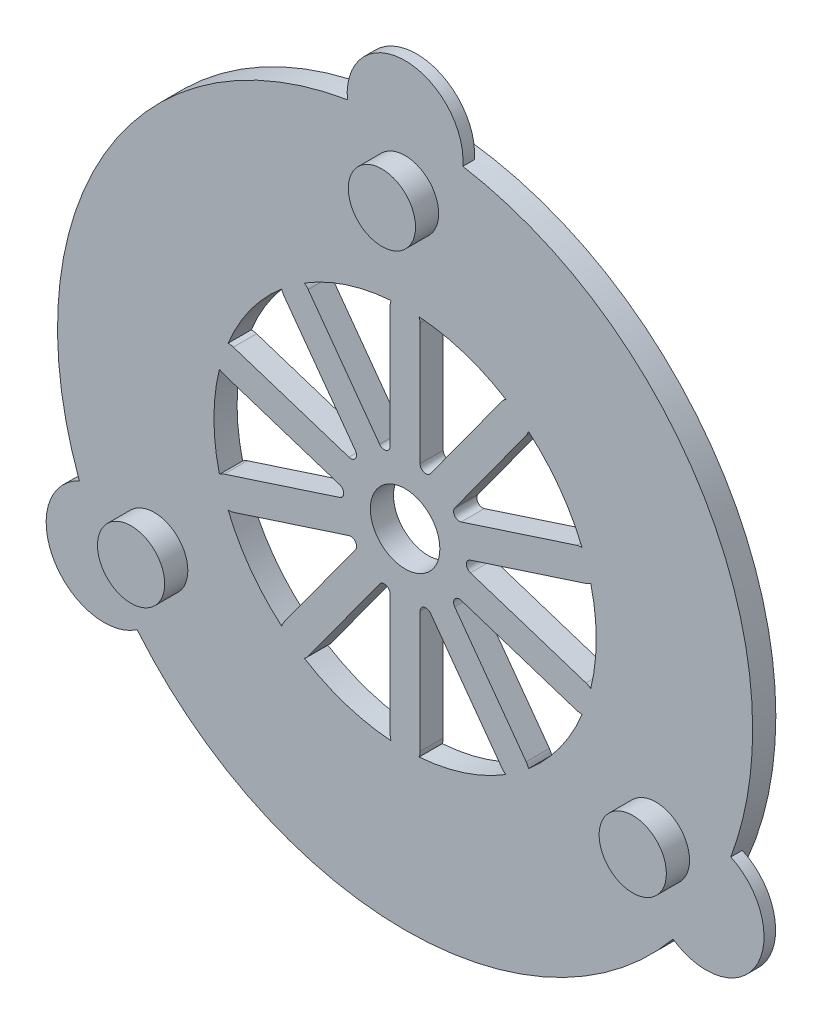
SolidWorks part; units mm, degrees
ref_plane "Спереди" through (0, 0, 0) normal (0, 0, 1) x (1, 0, 0)
ref_plane "Сверху" through (0, 0, 0) normal (0, 1, 0) x (1, 0, 0)
ref_plane "Справа" through (0, 0, 0) normal (1, 0, 0) x (0, 0, -1)
sketch "Sketch1" plane through (0, 0, 0) normal (0, 0, 1) x (1, 0, 0)
  line L0 (3.9, 6.755) -> (7.8, 0) construction
  line L2 (5.85, 10.1325) -> (11.7, 0) construction
  line L4 (7.8, 13.51) -> (15.6, 0) construction
  circle A61 centre (0, 0) radius 20
  circle A131 centre (0, 0) radius 1.25
  circle A484 centre (3.9, 0) radius 1.25
  circle A485 centre (7.8, 0) radius 1.25
  circle A486 centre (11.7, 0) radius 1.25
  circle A487 centre (15.6, 0) radius 1.25
  circle A488 centre (1.95, -3.3775) radius 1.25
  circle A489 centre (3.9, -6.755) radius 1.25
  circle A490 centre (5.85, -10.1325) radius 1.25
  circle A491 centre (7.8, -13.51) radius 1.25
  circle A492 centre (-1.95, -3.3775) radius 1.25
  circle A493 centre (-3.9, -6.755) radius 1.25
  circle A494 centre (-5.85, -10.1325) radius 1.25
  circle A495 centre (-7.8, -13.51) radius 1.25
  circle A496 centre (-3.9, 0) radius 1.25
  circle A497 centre (-7.8, 0) radius 1.25
  circle A498 centre (-11.7, 0) radius 1.25
  circle A499 centre (-15.6, 0) radius 1.25
  circle A500 centre (-1.95, 3.3775) radius 1.25
  circle A501 centre (-3.9, 6.755) radius 1.25
  circle A502 centre (-5.85, 10.1325) radius 1.25
  circle A503 centre (-7.8, 13.51) radius 1.25
  circle A504 centre (1.95, 3.3775) radius 1.25
  circle A505 centre (3.9, 6.755) radius 1.25
  circle A506 centre (5.85, 10.1325) radius 1.25
  circle A507 centre (7.8, 13.51) radius 1.25
  circle A508 centre (5.85, 3.3775) radius 1.25
  circle A509 centre (7.8, 6.755) radius 1.25
  circle A510 centre (9.75, 3.3775) radius 1.25
  circle A511 centre (11.7, 6.755) radius 1.25
  circle A512 centre (9.7491, 10.1341) radius 1.25
  circle A513 centre (13.6509, 3.3759) radius 1.25
  circle A514 centre (5.85, -3.3791) radius 1.25
  circle A515 centre (9.75, -3.3791) radius 1.25
  circle A516 centre (7.8, -6.7566) radius 1.25
  circle A517 centre (11.7, -6.7566) radius 1.25
  circle A518 centre (9.7491, -10.1356) radius 1.25
  circle A519 centre (13.6509, -3.3775) radius 1.25
  circle A520 centre (-0.0013, -6.7573) radius 1.25
  circle A521 centre (1.9487, -10.1348) radius 1.25
  circle A522 centre (-1.9513, -10.1348) radius 1.25
  circle A523 centre (-0.0013, -13.5123) radius 1.25
  circle A524 centre (-3.9032, -13.5123) radius 1.25
  circle A525 centre (3.9005, -13.5123) radius 1.25
  circle A526 centre (-5.8527, -3.3791) radius 1.25
  circle A527 centre (-7.8027, -6.7566) radius 1.25
  circle A528 centre (-9.7527, -3.3791) radius 1.25
  circle A529 centre (-11.7027, -6.7566) radius 1.25
  circle A530 centre (-13.6536, -3.3775) radius 1.25
  circle A531 centre (-9.7518, -10.1356) radius 1.25
  circle A532 centre (-5.8527, 3.3775) radius 1.25
  circle A533 centre (-9.7527, 3.3775) radius 1.25
  circle A534 centre (-7.8027, 6.755) radius 1.25
  circle A535 centre (-11.7027, 6.755) radius 1.25
  circle A536 centre (-9.7518, 10.1341) radius 1.25
  circle A537 centre (-13.6536, 3.3759) radius 1.25
  circle A538 centre (-0.0014, 6.7558) radius 1.25
  circle A539 centre (-1.9514, 10.1333) radius 1.25
  circle A540 centre (1.9486, 10.1333) radius 1.25
  circle A541 centre (-0.0014, 13.5108) radius 1.25
  circle A542 centre (3.9005, 13.5108) radius 1.25
  circle A543 centre (-3.9032, 13.5108) radius 1.25
  circle A544 centre (13.65, -1.1258) radius 2.2517 construction
  circle A545 centre (11.7009, -4.5044) radius 2.2522 construction
  circle A546 centre (9.75, -7.8834) radius 2.2522 construction
  circle A547 centre (7.7987, -11.2591) radius 2.2509 construction
  circle A548 centre (13.65, -1.1258) radius 0.65
  circle A549 centre (11.7009, -4.5044) radius 0.65
  circle A550 centre (9.75, -7.8834) radius 0.65
  circle A551 centre (7.7987, -11.2591) radius 0.65
  circle A552 centre (9.75, -1.1258) radius 0.65
  circle A553 centre (7.8009, -4.5044) radius 0.65
  circle A554 centre (5.85, -7.8834) radius 0.65
  circle A555 centre (3.8987, -11.2591) radius 0.65
  circle A556 centre (5.85, -1.1258) radius 0.65
  circle A557 centre (3.9009, -4.5044) radius 0.65
  circle A558 centre (1.95, -7.8834) radius 0.65
  circle A559 centre (-0.0013, -11.2591) radius 0.65
  circle A560 centre (1.95, -1.1258) radius 0.65
  circle A561 centre (0.0009, -4.5044) radius 0.65
  circle A562 centre (-1.95, -7.8834) radius 0.65
  circle A563 centre (-3.9013, -11.2591) radius 0.65
  circle A564 centre (-1.95, -1.1258) radius 0.65
  circle A565 centre (-3.8991, -4.5044) radius 0.65
  circle A566 centre (-5.85, -7.8834) radius 0.65
  circle A567 centre (-7.8013, -11.2591) radius 0.65
  circle A568 centre (-5.85, -1.1258) radius 0.65
  circle A569 centre (-7.7991, -4.5044) radius 0.65
  circle A570 centre (-9.75, -7.8834) radius 0.65
  circle A572 centre (-9.75, -1.1258) radius 0.65
  circle A573 centre (-11.6991, -4.5044) radius 0.65
  circle A576 centre (-13.65, -1.1258) radius 0.65
  circle A587 centre (0, 2.2517) radius 2.2517 construction
  circle A588 centre (0, 2.2517) radius 0.65
  circle A589 centre (3.9, 2.2517) radius 0.65
  circle A590 centre (7.8, 2.2517) radius 0.65
  circle A591 centre (11.7, 2.2517) radius 0.65
  circle A592 centre (15.6, 2.2517) radius 0.65
  circle A593 centre (1.9491, 5.6297) radius 2.2522 construction
  circle A594 centre (1.9491, 5.6297) radius 0.65
  circle A595 centre (5.8491, 5.6297) radius 0.65
  circle A596 centre (9.7491, 5.6297) radius 0.65
  circle A597 centre (13.6491, 5.6297) radius 0.65
  circle A598 centre (3.8991, 9.0072) radius 2.2522 construction
  circle A599 centre (3.8991, 9.0072) radius 0.65
  circle A600 centre (7.7991, 9.0072) radius 0.65
  circle A601 centre (11.6991, 9.0072) radius 0.65
  circle A602 centre (5.85, 12.3842) radius 2.2517 construction
  circle A603 centre (5.85, 12.3842) radius 0.65
  circle A604 centre (9.75, 12.3842) radius 0.65
  circle A605 centre (5.85, -14.6358) radius 0.65
  circle A606 centre (1.9509, -14.6353) radius 0.65
  circle A607 centre (-1.9491, -14.6353) radius 0.65
  circle A608 centre (-5.85, -14.6358) radius 0.65
  circle A609 centre (-15.6, 2.2517) radius 0.65
  circle A610 centre (-13.65, 5.6281) radius 0.65
  circle A611 centre (-11.7, 9.0056) radius 0.65
  circle A612 centre (-9.75, 12.3842) radius 0.65
  circle A613 centre (-5.85, 12.3842) radius 0.65
  circle A614 centre (-1.95, 12.3842) radius 0.65
  circle A615 centre (1.95, 12.3842) radius 0.65
  circle A616 centre (-7.8, 9.0056) radius 0.65
  circle A617 centre (-9.75, 5.6281) radius 0.65
  circle A618 centre (-11.7, 2.2517) radius 0.65
  circle A619 centre (-3.9, 9.0056) radius 0.65
  circle A620 centre (-5.85, 5.6281) radius 0.65
  circle A621 centre (-7.8, 2.2517) radius 0.65
  circle A622 centre (0, 9.0056) radius 0.65
  circle A623 centre (-1.95, 5.6281) radius 0.65
  circle A624 centre (-3.9, 2.2517) radius 0.65
  circle A625 centre (-15.5991, -4.5044) radius 0.65
  circle A626 centre (-13.65, -7.8834) radius 0.65
  circle A627 centre (-17.55, -7.8834) radius 0.65
  circle A628 centre (-19.5013, -11.2591) radius 0.65
  circle A629 centre (-15.6013, -11.2591) radius 0.65
  circle A630 centre (-11.7013, -11.2591) radius 0.65
  point P51 (0, 0)
  point P125 (-0.0013, -0.0008)
  point P231 (0, 0)
  dimension "D1" = 5
  dimension "D3" = 6
  dimension "D5" = 8
  dimension "D7" = 4
  dimension "D11" = 4
  dimension "D2" = 6
  dimension "D6" = 5
  dimension "D8" = 3
  dimension "D9" = 2
  dimension "D4" = 1.3
  dimension "D10" = 3
ref_plane "Plane1" through (0, 0, 10) normal (0, 0, 1) x (1, 0, 0)
sketch "Sketch2" plane through (0, 0, 10) normal (0, 0, 1) x (1, 0, 0)
  line L0 (-0.0032, 16) -> (0, 0) construction
  line L1 (1.2877, 16.0003) -> (1.2909, 0.0003)
  line L2 (-1.2941, 15.9997) -> (-1.2909, -0.0003)
  line L3 (8.3575, 13.7047) -> (-1.0445, 0.7585)
  line L4 (10.4465, 12.1876) -> (1.0445, -0.7585)
  line L5 (9.402, 12.9462) -> (0, 0) construction
  line L6 (14.8168, 6.1749) -> (-0.3991, 1.2276)
  line L7 (15.6151, 3.7197) -> (0.3991, -1.2276)
  line L8 (15.2159, 4.9473) -> (0, 0) construction
  line L9 (15.6165, -3.7135) -> (0.3987, 1.2278)
  line L10 (14.8192, -6.169) -> (-0.3987, -1.2278)
  line L11 (15.2179, -4.9412) -> (0, 0) construction
  line L12 (10.4513, -12.1834) -> (1.0442, 0.759)
  line L13 (8.363, -13.7014) -> (-1.0442, -0.759)
  line L14 (9.4072, -12.9424) -> (0, 0) construction
  line L15 (1.2941, -15.9997) -> (1.2909, 0.0003)
  line L16 (-1.2877, -16.0003) -> (-1.2909, -0.0003)
  line L17 (0.0032, -16) -> (0, 0) construction
  line L18 (-8.3575, -13.7047) -> (1.0445, -0.7585)
  line L19 (-10.4465, -12.1876) -> (-1.0445, 0.7585)
  line L20 (-9.402, -12.9462) -> (0, 0) construction
  line L21 (-14.8168, -6.1749) -> (0.3991, -1.2276)
  line L22 (-15.6151, -3.7197) -> (-0.3991, 1.2276)
  line L23 (-15.2159, -4.9473) -> (0, 0) construction
  line L24 (-15.6165, 3.7135) -> (-0.3987, -1.2278)
  line L25 (-14.8192, 6.169) -> (0.3987, 1.2278)
  line L26 (-15.2179, 4.9412) -> (0, 0) construction
  line L27 (-10.4513, 12.1834) -> (-1.0442, -0.759)
  line L28 (-8.363, 13.7014) -> (1.0442, 0.759)
  line L29 (-9.4072, 12.9424) -> (0, 0) construction
  circle A52 centre (0, 0) radius 16.85 construction
  circle A53 centre (0, 0) radius 18.85
  arc A54 (1.2877, 16.0003) -> (-1.2941, 15.9997) centre (-0.0032, 16) ccw
  arc A55 (-1.2909, -0.0003) -> (1.2909, 0.0003) centre (0, 0) ccw
  arc A56 (10.4465, 12.1876) -> (8.3575, 13.7047) centre (9.402, 12.9462) ccw
  arc A57 (-1.0445, 0.7585) -> (1.0445, -0.7585) centre (0, 0) ccw
  arc A58 (15.6151, 3.7197) -> (14.8168, 6.1749) centre (15.2159, 4.9473) ccw
  arc A59 (-0.3991, 1.2276) -> (0.3991, -1.2276) centre (0, 0) ccw
  arc A60 (14.8192, -6.169) -> (15.6165, -3.7135) centre (15.2179, -4.9412) ccw
  arc A61 (0.3987, 1.2278) -> (-0.3987, -1.2278) centre (0, 0) ccw
  arc A62 (8.363, -13.7014) -> (10.4513, -12.1834) centre (9.4072, -12.9424) ccw
  arc A63 (1.0442, 0.759) -> (-1.0442, -0.759) centre (0, 0) ccw
  arc A64 (-1.2877, -16.0003) -> (1.2941, -15.9997) centre (0.0032, -16) ccw
  arc A65 (1.2909, 0.0003) -> (-1.2909, -0.0003) centre (0, 0) ccw
  arc A66 (-10.4465, -12.1876) -> (-8.3575, -13.7047) centre (-9.402, -12.9462) ccw
  arc A67 (1.0445, -0.7585) -> (-1.0445, 0.7585) centre (0, 0) ccw
  arc A68 (-15.6151, -3.7197) -> (-14.8168, -6.1749) centre (-15.2159, -4.9473) ccw
  arc A69 (0.3991, -1.2276) -> (-0.3991, 1.2276) centre (0, 0) ccw
  arc A70 (-14.8192, 6.169) -> (-15.6165, 3.7135) centre (-15.2179, 4.9412) ccw
  arc A71 (-0.3987, -1.2278) -> (0.3987, 1.2278) centre (0, 0) ccw
  arc A72 (-8.363, 13.7014) -> (-10.4513, 12.1834) centre (-9.4072, 12.9424) ccw
  arc A73 (-1.0442, -0.759) -> (1.0442, 0.759) centre (0, 0) ccw
  point P1 (-0.0016, 8)
  point P9 (4.701, 6.4731)
  point P15 (7.608, 2.4737)
  point P21 (7.6089, -2.4706)
  point P27 (4.7036, -6.4712)
  point P33 (0.0016, -8)
  point P39 (-4.701, -6.4731)
  point P45 (-7.608, -2.4737)
  point P51 (-7.6089, 2.4706)
  point P57 (-4.7036, 6.4712)
  point P62 (0, 0)
extrude "Boss-Extrude1" add sketch "Sketch2" along normal blind 2 contours L4 A56 L3 L1 L6 | L1 A54 L2 L28 L3 | L28 A72 L27 L25 L2 | L25 A70 L24 L22 L27 | L22 A68 L21 L19 L24 | L19 A66 L18 L16 L21 | L16 A64 L15 L13 L18 | L13 A62 L12 L10 L15 | L10 A60 L9 L7 L12 | L7 A58 L6 L4 L9
sketch "Sketch3" plane through (0, 0, 12) normal (0, 0, 1) x (1, 0, 0)
  circle A0 centre (0, 0) radius 16.5
  circle A1 centre (0, 0) radius 30
extrude "Boss-Extrude2" add sketch "Sketch3" against normal blind 2
sketch "Sketch4" plane through (0, 0, 12) normal (0, 0, 1) x (1, 0, 0)
  circle A0 centre (0, 0) radius 25 construction
  circle A1 centre (0, 25) radius 2.9
  circle A2 centre (21.6506, -12.5) radius 2.9
  circle A3 centre (-21.6506, -12.5) radius 2.9
  point P11 (0, 0)
  dimension "D1" = 3
extrude "Boss-Extrude3" add sketch "Sketch4" along normal blind 2
sketch "Sketch6" plane through (0, 0, 11) normal (0, 0, -1) x (-1, 0, 0)
  circle A0 centre (0, 30) radius 5
  circle A2 centre (25.9808, -15) radius 5
  circle A3 centre (-25.9808, -15) radius 5
  point P10 (0, 0)
  dimension "D1" = 3
extrude "Boss-Extrude4" add sketch "Sketch6" against normal blind 1
sketch "Sketch5" plane through (0, 0, 10) normal (0, 0, -1) x (-1, 0, 0)
  circle A0 centre (0, 25) radius 3
  circle A1 centre (21.6506, -12.5) radius 3
  circle A2 centre (-21.6506, -12.5) radius 3
sketch "Sketch9" plane through (0, 0, 0) normal (0, 0, 1) x (1, 0, 0)
  line L0 (-7.8, 13.51) -> (-7.8027, 6.755) construction
  line L1 (-9.7518, 10.1341) -> (-5.85, 10.1325) construction
  line L2 (-7.8008, 11.6325) -> (-7.8019, 8.6325) construction
  line L3 (-6.8008, 11.6321) -> (-6.8019, 8.6321)
  line L4 (-8.8008, 11.6329) -> (-8.8019, 8.6329)
  line L5 (-4.9008, 11.6329) -> (-4.9019, 8.6329)
  line L6 (-2.9008, 11.6321) -> (-2.9019, 8.6321)
  line L7 (-3.9008, 11.6325) -> (-3.9019, 8.6325) construction
  line L8 (-1.0008, 11.6329) -> (-1.0019, 8.6329)
  line L9 (0.9992, 11.6321) -> (0.9981, 8.6321)
  line L10 (-0.0008, 11.6325) -> (-0.0019, 8.6325) construction
  line L11 (2.8992, 11.6329) -> (2.8981, 8.6329)
  line L12 (4.8992, 11.6321) -> (4.8981, 8.6321)
  line L13 (3.8992, 11.6325) -> (3.8981, 8.6325) construction
  line L14 (6.7992, 11.6329) -> (6.7981, 8.6329)
  line L15 (8.7992, 11.6321) -> (8.7981, 8.6321)
  line L16 (7.7992, 11.6325) -> (7.7981, 8.6325) construction
  line L17 (-9.7518, 10.1341) -> (-9.7527, 3.3775) construction
  line L18 (-11.7027, 6.755) -> (-7.8027, 6.755) construction
  line L19 (-10.7035, 1.877) -> (-10.702, 4.877)
  line L22 (-9.7527, 3.3775) -> (-5.8527, 3.3775) construction
  line L25 (-7.8027, 6.755) -> (-7.8, 0) construction
  line L26 (-7.8035, 1.8775) -> (-7.8019, 4.8775) construction
  line L27 (-8.8035, 1.878) -> (-8.8019, 4.878)
  line L28 (-6.8035, 1.877) -> (-6.8019, 4.877)
  line L29 (-2.9035, 1.877) -> (-2.9019, 4.877)
  line L30 (-4.9035, 1.878) -> (-4.9019, 4.878)
  line L31 (-3.9035, 1.8775) -> (-3.9019, 4.8775) construction
  line L32 (0.9965, 1.877) -> (0.9981, 4.877)
  line L33 (-1.0035, 1.878) -> (-1.0019, 4.878)
  line L34 (-0.0035, 1.8775) -> (-0.0019, 4.8775) construction
  line L35 (4.8965, 1.877) -> (4.8981, 4.877)
  line L36 (2.8965, 1.878) -> (2.8981, 4.878)
  line L37 (3.8965, 1.8775) -> (3.8981, 4.8775) construction
  line L38 (8.7965, 1.877) -> (8.7981, 4.877)
  line L39 (6.7965, 1.878) -> (6.7981, 4.878)
  line L40 (7.7965, 1.8775) -> (7.7981, 4.8775) construction
  line L41 (12.6965, 1.877) -> (12.6981, 4.877)
  line L42 (10.6965, 1.878) -> (10.6981, 4.878)
  line L43 (11.6965, 1.8775) -> (11.6981, 4.8775) construction
  line L44 (-12.7035, 1.878) -> (-12.7019, 4.878)
  line L45 (-11.7035, 1.8775) -> (-11.702, 4.8775) construction
  line L46 (-9.7527, -3.3791) -> (-5.8527, -3.3791) construction
  line L47 (-7.8, 0) -> (-7.8027, -6.7566) construction
  line L48 (-7.8046, -4.8791) -> (-7.8008, -1.8791) construction
  line L49 (-8.8046, -4.8778) -> (-8.8008, -1.8778)
  line L50 (-6.8046, -4.8804) -> (-6.8008, -1.8804)
  line L51 (-2.9046, -4.8804) -> (-2.9008, -1.8804)
  line L52 (-4.9046, -4.8778) -> (-4.9008, -1.8778)
  line L53 (-3.9046, -4.8791) -> (-3.9008, -1.8791) construction
  line L54 (0.9954, -4.8804) -> (0.9992, -1.8804)
  line L55 (-1.0046, -4.8778) -> (-1.0008, -1.8778)
  line L56 (-0.0046, -4.8791) -> (-0.0008, -1.8791) construction
  line L57 (4.8954, -4.8804) -> (4.8992, -1.8804)
  line L58 (2.8954, -4.8778) -> (2.8992, -1.8778)
  line L59 (3.8954, -4.8791) -> (3.8992, -1.8791) construction
  line L60 (8.7954, -4.8804) -> (8.7992, -1.8804)
  line L61 (6.7954, -4.8778) -> (6.7992, -1.8778)
  line L62 (7.7954, -4.8791) -> (7.7992, -1.8791) construction
  line L63 (12.6954, -4.8804) -> (12.6992, -1.8804)
  line L64 (10.6954, -4.8778) -> (10.6992, -1.8778)
  line L65 (11.6954, -4.8791) -> (11.6992, -1.8791) construction
  line L66 (-10.7046, -4.8804) -> (-10.7008, -1.8804)
  line L67 (-12.7046, -4.8778) -> (-12.7008, -1.8778)
  line L68 (-11.7046, -4.8791) -> (-11.7008, -1.8791) construction
  line L69 (-9.7518, -10.1356) -> (-5.482, -10.1356) construction
  line L70 (-7.8027, -6.7566) -> (-7.8, -13.51) construction
  line L71 (-7.8007, -8.6356) -> (-7.8007, -11.6356) construction
  line L72 (-6.8007, -8.6356) -> (-6.8007, -11.6356)
  line L73 (-8.8007, -8.6356) -> (-8.8007, -11.6356)
  line L74 (-4.9007, -8.6356) -> (-4.9007, -11.6356)
  line L75 (-2.9007, -8.6356) -> (-2.9007, -11.6356)
  line L76 (-3.9007, -8.6356) -> (-3.9007, -11.6356) construction
  line L77 (-1.0007, -8.6356) -> (-1.0007, -11.6356)
  line L78 (0.9993, -8.6356) -> (0.9993, -11.6356)
  line L79 (-0.0007, -8.6356) -> (-0.0007, -11.6356) construction
  line L80 (2.8993, -8.6356) -> (2.8993, -11.6356)
  line L81 (4.8993, -8.6356) -> (4.8993, -11.6356)
  line L82 (3.8993, -8.6356) -> (3.8993, -11.6356) construction
  line L83 (6.7993, -8.6356) -> (6.7993, -11.6356)
  line L84 (8.7993, -8.6356) -> (8.7993, -11.6356)
  line L85 (7.7993, -8.6356) -> (7.7993, -11.6356) construction
  arc A0 (-6.8008, 11.6321) -> (-8.8008, 11.6329) centre (-7.8008, 11.6325) ccw
  arc A1 (-8.8019, 8.6329) -> (-6.8019, 8.6321) centre (-7.8019, 8.6325) ccw
  arc A2 (-2.9008, 11.6321) -> (-4.9008, 11.6329) centre (-3.9008, 11.6325) ccw
  arc A3 (-4.9019, 8.6329) -> (-2.9019, 8.6321) centre (-3.9019, 8.6325) ccw
  arc A4 (0.9992, 11.6321) -> (-1.0008, 11.6329) centre (-0.0008, 11.6325) ccw
  arc A5 (-1.0019, 8.6329) -> (0.9981, 8.6321) centre (-0.0019, 8.6325) ccw
  arc A6 (4.8992, 11.6321) -> (2.8992, 11.6329) centre (3.8992, 11.6325) ccw
  arc A7 (2.8981, 8.6329) -> (4.8981, 8.6321) centre (3.8981, 8.6325) ccw
  arc A8 (8.7992, 11.6321) -> (6.7992, 11.6329) centre (7.7992, 11.6325) ccw
  arc A9 (6.7981, 8.6329) -> (8.7981, 8.6321) centre (7.7981, 8.6325) ccw
  arc A14 (-8.8035, 1.878) -> (-6.8035, 1.877) centre (-7.8035, 1.8775) ccw
  arc A15 (-6.8019, 4.877) -> (-8.8019, 4.878) centre (-7.8019, 4.8775) ccw
  arc A16 (-4.9035, 1.878) -> (-2.9035, 1.877) centre (-3.9035, 1.8775) ccw
  arc A17 (-2.9019, 4.877) -> (-4.9019, 4.878) centre (-3.9019, 4.8775) ccw
  arc A18 (-1.0035, 1.878) -> (0.9965, 1.877) centre (-0.0035, 1.8775) ccw
  arc A19 (0.9981, 4.877) -> (-1.0019, 4.878) centre (-0.0019, 4.8775) ccw
  arc A20 (2.8965, 1.878) -> (4.8965, 1.877) centre (3.8965, 1.8775) ccw
  arc A21 (4.8981, 4.877) -> (2.8981, 4.878) centre (3.8981, 4.8775) ccw
  arc A22 (6.7965, 1.878) -> (8.7965, 1.877) centre (7.7965, 1.8775) ccw
  arc A23 (8.7981, 4.877) -> (6.7981, 4.878) centre (7.7981, 4.8775) ccw
  arc A24 (10.6965, 1.878) -> (12.6965, 1.877) centre (11.6965, 1.8775) ccw
  arc A25 (12.6981, 4.877) -> (10.6981, 4.878) centre (11.6981, 4.8775) ccw
  arc A26 (-12.7035, 1.878) -> (-10.7035, 1.877) centre (-11.7035, 1.8775) ccw
  arc A27 (-10.702, 4.877) -> (-12.7019, 4.878) centre (-11.702, 4.8775) ccw
  arc A28 (-8.8046, -4.8778) -> (-6.8046, -4.8804) centre (-7.8046, -4.8791) ccw
  arc A29 (-6.8008, -1.8804) -> (-8.8008, -1.8778) centre (-7.8008, -1.8791) ccw
  arc A30 (-4.9046, -4.8778) -> (-2.9046, -4.8804) centre (-3.9046, -4.8791) ccw
  arc A31 (-2.9008, -1.8804) -> (-4.9008, -1.8778) centre (-3.9008, -1.8791) ccw
  arc A32 (-1.0046, -4.8778) -> (0.9954, -4.8804) centre (-0.0046, -4.8791) ccw
  arc A33 (0.9992, -1.8804) -> (-1.0008, -1.8778) centre (-0.0008, -1.8791) ccw
  arc A34 (2.8954, -4.8778) -> (4.8954, -4.8804) centre (3.8954, -4.8791) ccw
  arc A35 (4.8992, -1.8804) -> (2.8992, -1.8778) centre (3.8992, -1.8791) ccw
  arc A36 (6.7954, -4.8778) -> (8.7954, -4.8804) centre (7.7954, -4.8791) ccw
  arc A37 (8.7992, -1.8804) -> (6.7992, -1.8778) centre (7.7992, -1.8791) ccw
  arc A38 (10.6954, -4.8778) -> (12.6954, -4.8804) centre (11.6954, -4.8791) ccw
  arc A39 (12.6992, -1.8804) -> (10.6992, -1.8778) centre (11.6992, -1.8791) ccw
  arc A40 (-12.7046, -4.8778) -> (-10.7046, -4.8804) centre (-11.7046, -4.8791) ccw
  arc A41 (-10.7008, -1.8804) -> (-12.7008, -1.8778) centre (-11.7008, -1.8791) ccw
  arc A42 (-6.8007, -8.6356) -> (-8.8007, -8.6356) centre (-7.8007, -8.6356) ccw
  arc A43 (-8.8007, -11.6356) -> (-6.8007, -11.6356) centre (-7.8007, -11.6356) ccw
  arc A44 (-2.9007, -8.6356) -> (-4.9007, -8.6356) centre (-3.9007, -8.6356) ccw
  arc A45 (-4.9007, -11.6356) -> (-2.9007, -11.6356) centre (-3.9007, -11.6356) ccw
  arc A46 (0.9993, -8.6356) -> (-1.0007, -8.6356) centre (-0.0007, -8.6356) ccw
  arc A47 (-1.0007, -11.6356) -> (0.9993, -11.6356) centre (-0.0007, -11.6356) ccw
  arc A48 (4.8993, -8.6356) -> (2.8993, -8.6356) centre (3.8993, -8.6356) ccw
  arc A49 (2.8993, -11.6356) -> (4.8993, -11.6356) centre (3.8993, -11.6356) ccw
  arc A50 (8.7993, -8.6356) -> (6.7993, -8.6356) centre (7.7993, -8.6356) ccw
  arc A51 (6.7993, -11.6356) -> (8.7993, -11.6356) centre (7.7993, -11.6356) ccw
  circle A52 centre (0, 0) radius 16.85 construction
  circle A53 centre (0, 0) radius 18.85
  point P10 (-7.8014, 10.1325)
  point P18 (-3.9014, 10.1325)
  point P25 (-0.0014, 10.1325)
  point P32 (3.8986, 10.1325)
  point P39 (7.7986, 10.1325)
  point P50 (-11.7027, 3.3775)
  point P58 (-7.8027, 3.3775)
  point P68 (-3.9027, 3.3775)
  point P75 (-0.0027, 3.3775)
  point P82 (3.8973, 3.3775)
  point P89 (7.7973, 3.3775)
  point P96 (11.6973, 3.3775)
  point P108 (-7.8027, -3.3791)
  point P116 (-3.9027, -3.3791)
  point P123 (-0.0027, -3.3791)
  point P130 (3.8973, -3.3791)
  point P137 (7.7973, -3.3791)
  point P144 (11.6973, -3.3791)
  point P151 (-11.7027, -3.3791)
  point P162 (-7.8007, -10.1356)
  point P170 (-3.9007, -10.1356)
  point P177 (-0.0007, -10.1356)
  point P184 (3.8993, -10.1356)
  point P191 (7.7993, -10.1356)
  dimension "D1" = 2
  dimension "D15" = 2
  dimension "D2" = 3
  dimension "D4" = 2
  dimension "D5" = 3
  dimension "D6" = 2
  dimension "D7" = 3
  dimension "D9" = 2
  dimension "D12" = 3
  dimension "D13" = 2
  dimension "D3" = 5
  dimension "D8" = 6
  dimension "D10" = 6
  dimension "D11" = 2
  dimension "D14" = 5
sketch "Sketch10" plane through (0, 0, 20) normal (0, 0, 1) x (1, 0, 0)
  line L1 (-9.8683, 13.2069) -> (9.8683, 13.2069)
  line L2 (-9.8683, 13.2069) -> (-9.8683, -13.2069)
  line L3 (-9.8683, -13.2069) -> (9.8683, -13.2069)
  line L4 (9.8683, 13.2069) -> (9.8683, -13.2069)
  line L5 (-9.8683, 13.2069) -> (9.8683, -13.2069) construction
  line L6 (-9.8683, -13.2069) -> (9.8683, 13.2069) construction
  line L7 (-14.0535, 6.7065) -> (14.0535, 6.7065)
  line L8 (-14.0535, 6.7065) -> (-14.0535, -6.7065)
  line L9 (-14.0535, -6.7065) -> (14.0535, -6.7065)
  line L10 (14.0535, 6.7065) -> (14.0535, -6.7065)
  line L11 (-14.0535, 6.7065) -> (14.0535, -6.7065) construction
  line L12 (-14.0535, -6.7065) -> (14.0535, 6.7065) construction
  circle A0 centre (0, 0) radius 21.6778
  point P0 (0, 0)
  point P6 (0, 0)
fillet "Fillet1" [suppressed] radius 0.5
sketch "Sketch12" plane through (0, 0, 10) normal (0, 0, -1) x (-1, 0, 0)
  line L0 (-1.9972, -6.0904) -> (1.9972, 6.0904) construction
  line L3 (-2.4723, -5.9346) -> (1.5221, 6.2462)
  line L4 (-1.5221, -6.2462) -> (2.4723, 5.9346)
  line L5 (-6.4109, -0.4826) -> (6.4082, -0.5174)
  line L6 (-6.4082, 0.5174) -> (6.4109, 0.4826)
  line L7 (-6.4095, 0.0174) -> (6.4095, -0.0174) construction
  line L8 (-2.44, 5.948) -> (1.4881, -6.2544)
  line L9 (-1.4881, 6.2544) -> (2.44, -5.948)
  line L10 (-1.9641, 6.1012) -> (1.9641, -6.1012) construction
  line L11 (4.9029, 4.1586) -> (-5.4885, -3.348)
  line L12 (5.4885, 3.348) -> (-4.9029, -4.1586)
  line L13 (5.1957, 3.7533) -> (-5.1957, -3.7533) construction
  line L14 (5.4702, -3.3778) -> (-4.8802, 4.1852)
  line L15 (4.8802, -4.1852) -> (-5.4702, 3.3778)
  line L16 (5.1752, -3.7815) -> (-5.1752, 3.7815) construction
  circle A2 centre (0, 0) radius 3
  arc A3 (-2.4723, -5.9346) -> (-1.5221, -6.2462) centre (-1.9972, -6.0904) ccw
  arc A4 (2.4723, 5.9346) -> (1.5221, 6.2462) centre (1.9972, 6.0904) ccw
  arc A5 (-6.4082, 0.5174) -> (-6.4109, -0.4826) centre (-6.4095, 0.0174) ccw
  arc A6 (6.4082, -0.5174) -> (6.4109, 0.4826) centre (6.4095, -0.0174) ccw
  arc A7 (-1.4881, 6.2544) -> (-2.44, 5.948) centre (-1.9641, 6.1012) ccw
  arc A8 (1.4881, -6.2544) -> (2.44, -5.948) centre (1.9641, -6.1012) ccw
  arc A9 (5.4885, 3.348) -> (4.9029, 4.1586) centre (5.1957, 3.7533) ccw
  arc A10 (-5.4885, -3.348) -> (-4.9029, -4.1586) centre (-5.1957, -3.7533) ccw
  arc A11 (4.8802, -4.1852) -> (5.4702, -3.3778) centre (5.1752, -3.7815) ccw
  arc A12 (-4.8802, 4.1852) -> (-5.4702, 3.3778) centre (-5.1752, 3.7815) ccw
  point P5 (0, 0)
  point P15 (0, 0)
  point P22 (0, 0)
  point P29 (0, 0)
  point P36 (0, 0)
  point P41 (0, 0)
  dimension "D1" = 1
extrude "Boss-Extrude5" [suppressed] add sketch "Sketch12" against normal blind 2
sketch "Sketch13" plane through (0, 0, 10) normal (0, 0, -1) x (-1, 0, 0)
  circle A0 centre (0, 0) radius 4.1773
extrude "Boss-Extrude6" add sketch "Sketch13" against normal blind 2
fillet "Fillet2" radius 0.5 10 edges at (-1.2917, 3.9726, 11) (-3.38, 2.4547, 11) (-4.1773, -0.0008, 11) (-3.379, -2.456, 11) (-1.2901, -3.9731, 11) (1.2917, -3.9726, 11) (3.38, -2.4547, 11) (4.1773, 0.0008, 11) (3.379, 2.456, 11) (1.2901, 3.9731, 11)
sketch "Sketch14" plane through (0, 0, 10) normal (0, 0, -1) x (-1, 0, 0)
  circle A0 centre (0, 0) radius 3
extrude "Cut-Extrude1" cut sketch "Sketch14" against normal blind 20
